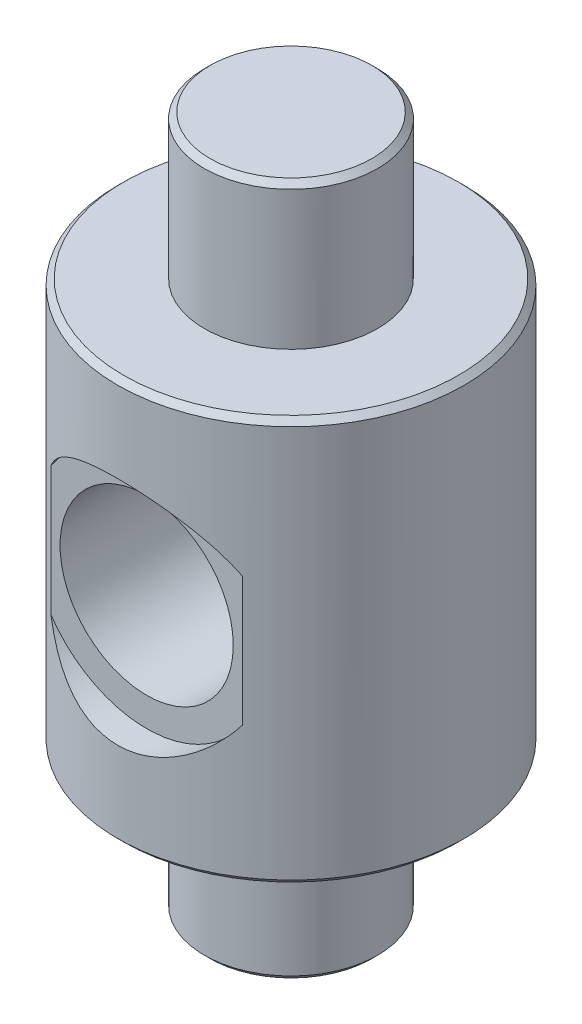
SolidWorks part; units mm, degrees
ref_plane "Front Plane" through (0, 0, 0) normal (0, 0, 1) x (1, 0, 0)
ref_plane "Top Plane" through (0, 0, 0) normal (0, 1, 0) x (1, 0, 0)
ref_plane "Right Plane" through (0, 0, 0) normal (1, 0, 0) x (0, 0, -1)
sketch "Sketch2" plane through (0, 0, 0) normal (0, 0, 1) x (1, 0, 0)
  line L0 (0, 0) -> (0, 12)
  line L1 (0, 12) -> (1.5, 12)
  line L2 (1.5, 12) -> (1.5, 9.5)
  line L3 (1.5, 9.5) -> (3, 9.5)
  line L4 (3, 9.5) -> (3, 2.5)
  line L5 (3, 2.5) -> (1.5, 2.5)
  line L6 (1.5, 2.5) -> (1.5, 0)
  line L7 (1.5, 0) -> (0, 0)
  dimension "D1" = 12
  dimension "D2" = 1.5
  dimension "D3" = 1.5
  dimension "D4" = 2.5
  dimension "D5" = 7
  dimension "D6" = 3
revolve "Revolve1" add sketch "Sketch2" angle 360 about L0
ref_plane "Plane1" through (0, 0, 3) normal (0, 0, 1) x (1, 0, 0)
sketch "Sketch3" plane through (0, 0, 3) normal (0, 0, 1) x (1, 0, 0)
  circle A0 centre (0, 6) radius 2
  dimension "D1" = 4
  dimension "D2" = 6
extrude "Cut-Extrude2" cut sketch "Sketch3" against normal blind 0.5
mirror "Mirror1" about plane through (0, 0, 0) normal (0, 0, 1) of "Cut-Extrude2"
sketch "Sketch5" plane through (0, 0, 2.5) normal (0, 0, 1) x (1, 0, 0)
  circle A0 centre (0, 6) radius 2
  circle A1 centre (0, 6) radius 1.5
  dimension "D1" = 3
extrude "Cut-Extrude3" cut sketch "Sketch5" against normal through all contours A1
chamfer "Chamfer1" distance 0.1 angle 45 4 edges at (0, 0, -1.5) (0, 2.5, -3) (0, 9.5, -3) (0, 12, -1.5)
